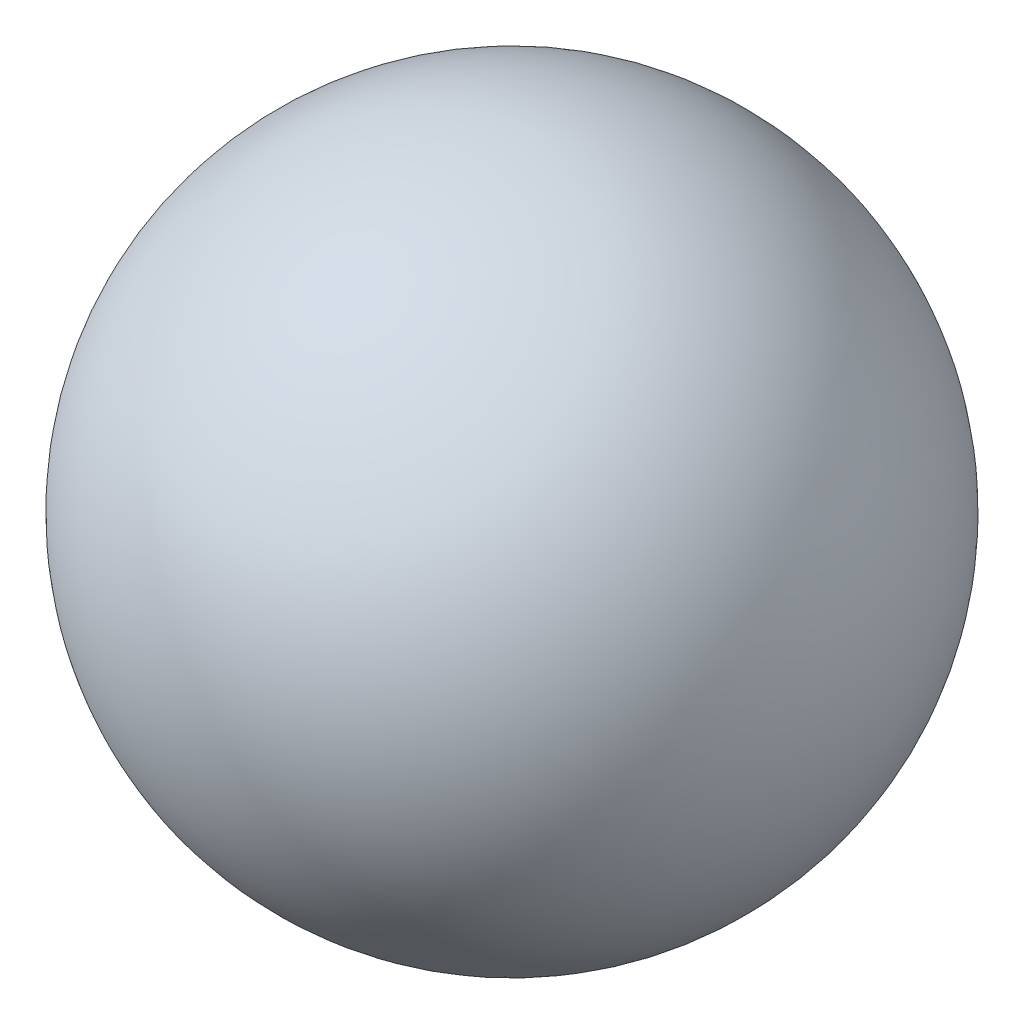
SolidWorks part; units mm, degrees
material "Custom Plastic"
ref_plane "Front" through (0, 0, 0) normal (0, 0, 1) x (1, 0, 0)
ref_plane "Top" through (0, 0, 0) normal (0, 1, 0) x (1, 0, 0)
ref_plane "Right" through (0, 0, 0) normal (1, 0, 0) x (0, 0, -1)
sketch "Sketch2" plane through (0, 0, 0) normal (0, 1, 0) x (1, 0, 0)
  line L0 (0, 110) -> (0, -110)
  arc A0 (0, 110) -> (0, -110) centre (0, 0) ccw
  dimension "D1" = 220
revolve "Revolve2" add sketch "Sketch2" angle 360 about L0
